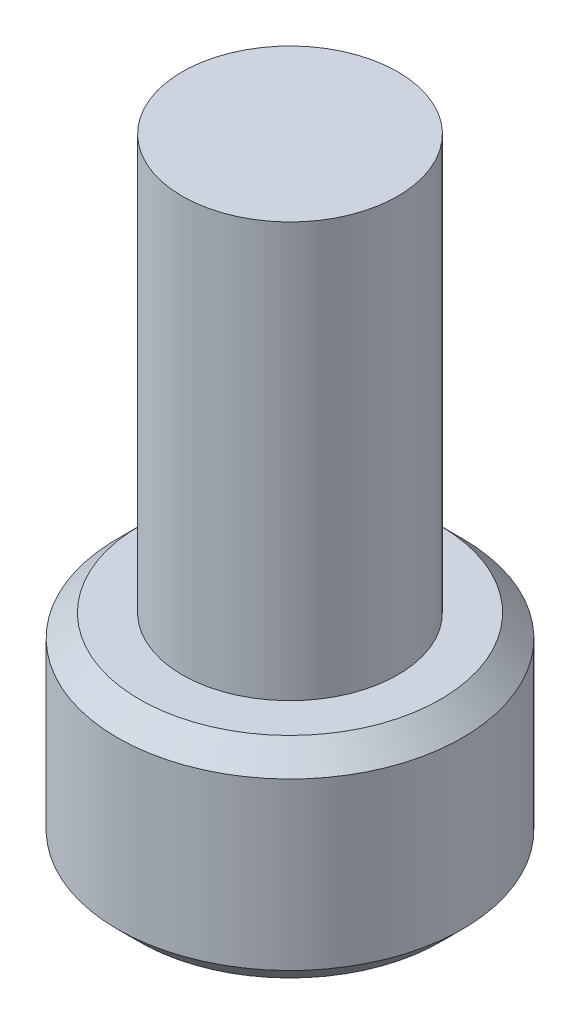
SolidWorks part; units mm, degrees
ref_plane "Front Plane" through (0, 0, 0) normal (0, 0, 1) x (1, 0, 0)
ref_plane "Top Plane" through (0, 0, 0) normal (0, 1, 0) x (1, 0, 0)
ref_plane "Right Plane" through (0, 0, 0) normal (1, 0, 0) x (0, 0, -1)
sketch "Sketch1" plane through (0, 0, 0) normal (0, 1, 0) x (1, 0, 0)
  circle A0 centre (0, 0) radius 2.4765
  dimension "D1" = 4.953
extrude "Boss-Extrude1" add sketch "Sketch1" along normal blind 9.525
sketch "Sketch2" plane through (0, 0, 0) normal (0, -1, 0) x (1, 0, 0)
  circle A0 centre (0, 0) radius 3.9624
  point P3 (0, 0)
  dimension "D1" = 7.9248
extrude "Boss-Extrude2" add sketch "Sketch2" along normal blind 4.826
sketch "Sketch3" plane through (0, -4.826, 0) normal (0, -1, 0) x (1, 0, 0)
  line L1 (2.2914, 0) -> (1.1457, 1.9844)
  line L2 (1.1457, 1.9844) -> (-1.1457, 1.9844)
  line L3 (-1.1457, 1.9844) -> (-2.2914, 0)
  line L4 (-2.2914, 0) -> (-1.1457, -1.9844)
  line L5 (-1.1457, -1.9844) -> (1.1457, -1.9844)
  line L6 (1.1457, -1.9844) -> (2.2914, 0)
  circle A0 centre (0, 0) radius 1.9844 construction
  point P1 (0, 0)
  dimension "D1" = 3.9688
extrude "Cut-Extrude1" cut sketch "Sketch3" against normal blind 2.286
chamfer "Chamfer1" distance 0.508 angle 45 2 edges at (0, -4.826, -3.9624) (0, 0, -3.9624)
